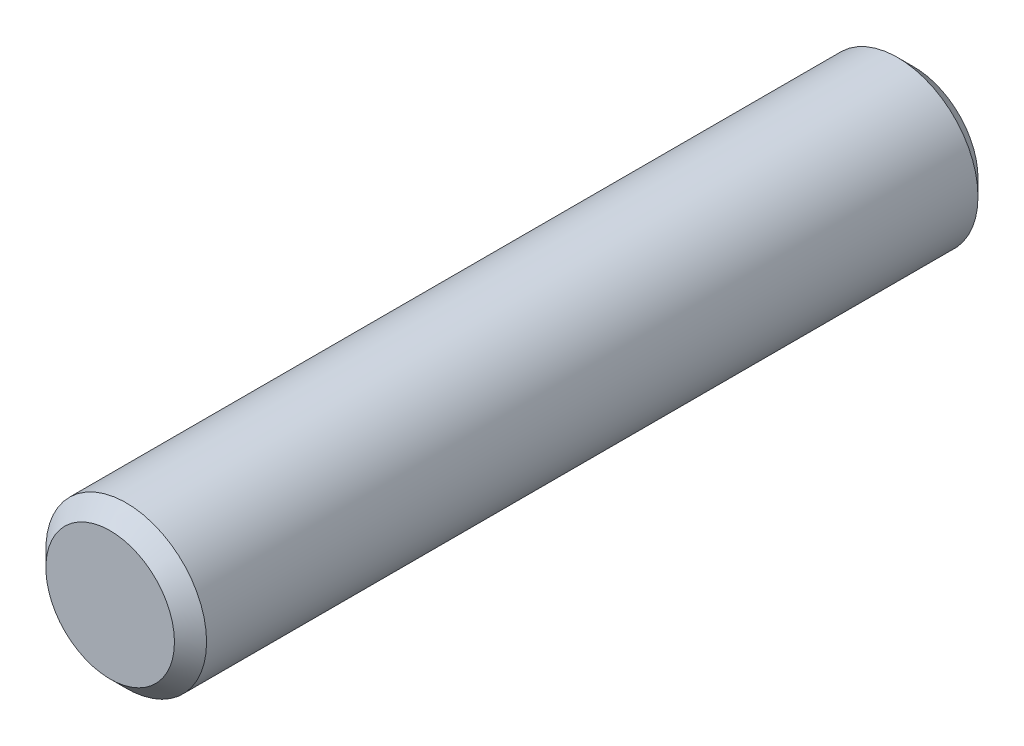
SolidWorks part; units mm, degrees
ref_plane "Front Plane" through (0, 0, 0) normal (0, 0, 1) x (1, 0, 0)
ref_plane "Top Plane" through (0, 0, 0) normal (0, 1, 0) x (1, 0, 0)
ref_plane "Right Plane" through (0, 0, 0) normal (1, 0, 0) x (0, 0, -1)
sketch "Sketch1" plane through (0, 0, 0) normal (0, 0, 1) x (1, 0, 0)
  circle A0 centre (0, 0) radius 1.27
  dimension "D1" = 2.54
extrude "Extrude1" add sketch "Sketch1" along normal mid plane 12.7
chamfer "Chamfer1" distance 0.254 angle 45 2 edges at (1.27, 0, -6.35) (1.27, 0, 6.35)
